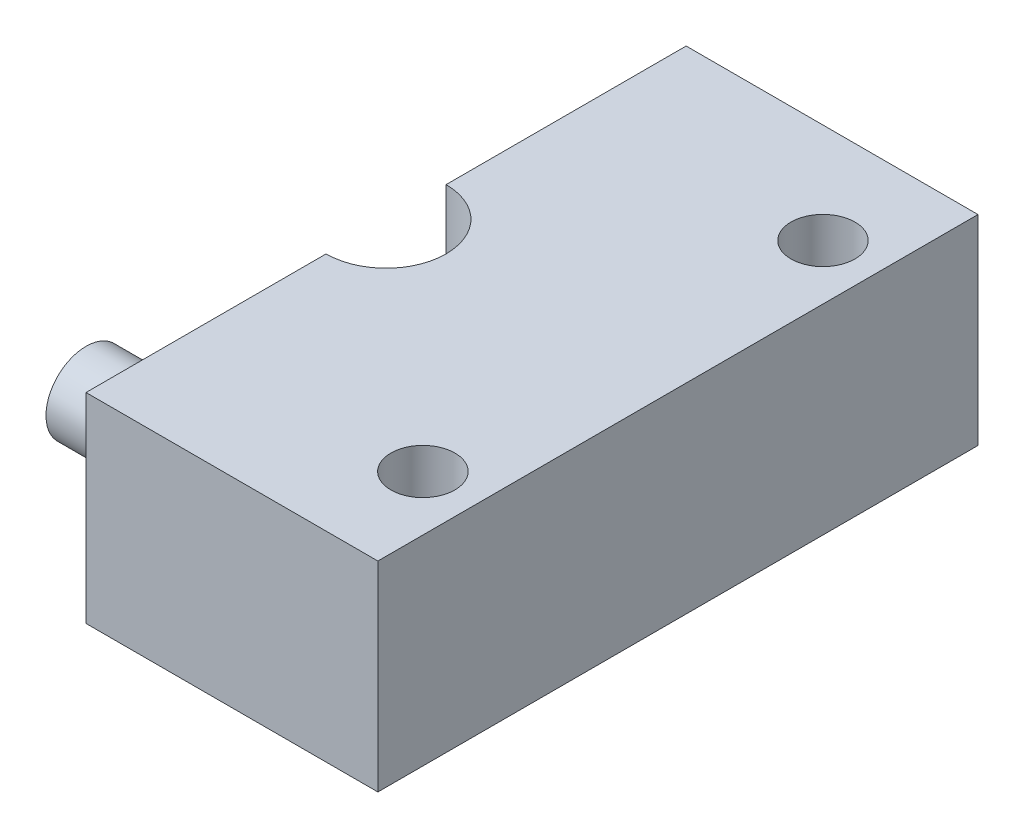
SolidWorks part; units mm, degrees
ref_plane "Ön Düzlem" through (0, 0, 0) normal (0, 0, 1) x (1, 0, 0)
ref_plane "Üst Düzlem" through (0, 0, 0) normal (0, 1, 0) x (1, 0, 0)
ref_plane "Sağ Düzlem" through (0, 0, 0) normal (1, 0, 0) x (0, 0, -1)
sketch "Sketch1" plane through (0, 0, 0) normal (0, 0, 1) x (1, 0, 0)
  line L0 (0, 0) -> (14.59, 0)
  line L1 (14.59, 0) -> (14.59, 10)
  line L2 (14.59, 10) -> (0, 10)
  line L3 (0, 10) -> (0, 0)
  dimension "D1" = 14.59
  dimension "D2" = 10
extrude "Boss-Extrude1" add sketch "Sketch1" along normal blind 30
sketch "Sketch2" plane through (0, 0, 0) normal (0, -1, 0) x (1, 0, 0)
  line L0 (0, 0) -> (14.59, 0) construction
  line L1 (14.59, 30) -> (14.59, 0) construction
  line L2 (0, 21) -> (3.5075, 21)
  line L3 (0, 30) -> (0, 0) construction
  line L4 (0, 9) -> (3.5075, 9)
  line L5 (0, 21) -> (0, 9)
  arc A0 (3.5075, 9) -> (3.5075, 21) centre (0, 15) ccw
  dimension "D3" = 13.9
  dimension "D1" = 15
  dimension "D2" = 14.59
  dimension "D4" = 12
extrude "Cut-Extrude1" cut sketch "Sketch2" against normal blind 3
sketch "Sketch3" plane through (0, 10, 0) normal (0, 1, 0) x (1, 0, 0)
  line L0 (14.59, 0) -> (0, 0) construction
  line L1 (14.59, -30) -> (14.59, 0) construction
  line L2 (14.59, -30) -> (0, -30) construction
  circle A0 centre (11.84, -5) radius 1.6
  circle A1 centre (11.84, -25) radius 1.6
  dimension "D3" = 3.2
  dimension "D1" = 5
  dimension "D2" = 2.75
  dimension "D4" = 5
extrude "Cut-Extrude2" cut sketch "Sketch3" against normal up to surface (10 mm away) up to face at (4.9547, 0, 15)
sketch "Sketch4" plane through (0, 10, 0) normal (0, 1, 0) x (1, 0, 0)
  line L0 (0, -30) -> (0, 0) construction
  line L1 (0, -12) -> (0, -18)
  arc A0 (0, -18) -> (0, -12) centre (0, -15) ccw
  dimension "D1" = 6
  dimension "D2" = 15
extrude "Cut-Extrude3" cut sketch "Sketch4" against normal up to surface (7 mm away) up to face at (2.6144, 3, 15)
sketch "Sketch5" plane through (0, 0, 0) normal (-1, 0, 0) x (0, 0, 1)
  line L1 (30, 0) -> (21, 0) construction
  line L2 (30, 10) -> (30, 0) construction
  circle A0 centre (25, 5) radius 2
  dimension "D1" = 4
  dimension "D2" = 5
  dimension "D3" = 5
extrude "Boss-Extrude2" add sketch "Sketch5" along normal blind 5
fillet "Fillet1" radius 1 1 edges at (0, 5, 23)
sketch "Sketch6" plane through (0, 0, 0) normal (-1, 0, 0) x (0, 0, 1)
  line L0 (0, 10) -> (0, 0) construction
  line L1 (9, 0) -> (0, 0) construction
  circle A0 centre (5, 5) radius 2.075
  dimension "D3" = 4.15
  dimension "D1" = 5
  dimension "D2" = 5
extrude "Cut-Extrude4" cut sketch "Sketch6" against normal blind 5
fillet "Fillet2" radius 1 1 edges at (0, 5, 7.075)
